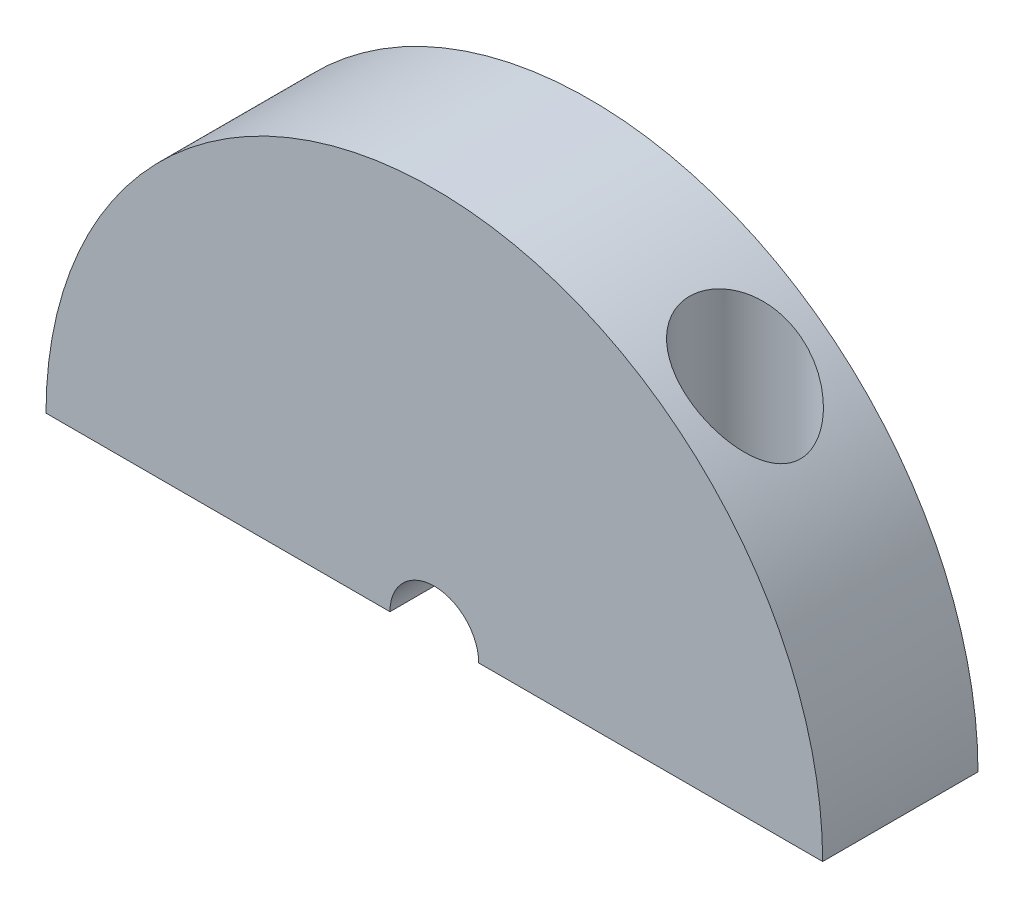
SolidWorks part; units mm, degrees
ref_plane "Plan de face" through (0, 0, 0) normal (0, 0, 1) x (1, 0, 0)
ref_plane "Plan de dessus" through (0, 0, 0) normal (0, 1, 0) x (1, 0, 0)
ref_plane "Plan de droite" through (0, 0, 0) normal (1, 0, 0) x (0, 0, -1)
sketch "Esquisse1" plane through (0, 0, 0) normal (0, 0, 1) x (1, 0, 0)
  line L0 (-1.7321, 1) -> (1.7321, 1)
  line L1 (0, 0) -> (17.5, 0)
  line L6 (17.5, 0) -> (-17.5, 0)
  circle A1 centre (0, 0) radius 2
  circle A2 centre (0, 0) radius 17.5
  dimension "D2" = 4
  dimension "D7" = 35
  dimension "D3" = 1
extrude "Boss.-Extru.1" add sketch "Esquisse1" along normal blind 5
sketch "Esquisse3" plane through (0, 0, 0) normal (0, 0, -1) x (-1, 0, 0)
  line L0 (0, 17.5) -> (0, -17.5)
  line L1 (-17.5, 0) -> (17.5, 0)
  circle A0 centre (0, 0) radius 17.5
  circle A1 centre (0, 0) radius 2
  point P9 (0, 0)
  arc M3 (1.7321, 1) -> (2, 0) centre (0, 0) cw
  arc M5 (17.5, 0) -> (-17.5, 0) centre (0, 0) ccw
  line M9 (-17.5, 0) -> (-2, 0)
  arc M10 (-2, 0) -> (-1.7321, 1) centre (0, 0) cw
  line M11 (2, 0) -> (17.5, 0)
extrude "Boss.-Extru.3" add sketch "Esquisse3" along normal blind 2 contours A1 L0 M5 M9 M10 | A1 L0 M3 M11 M5
sketch "Esquisse5" plane through (0, 0, 0) normal (0, -1, 0) x (1, 0, 0)
  line L0 (2, 5) -> (17.5, 5) construction
  line L1 (-2, 5) -> (-17.5, 5) construction
  line L2 (-17.5, 5) -> (-17.5, -2) construction
  line L3 (17.5, 5) -> (17.5, -2) construction
  circle A0 centre (-10.5, 1.5) radius 0.5
  circle A1 centre (10.5, 1.5) radius 2.5
  dimension "D1" = 1
  dimension "D2" = 5
  dimension "D3" = 3.5
  dimension "D4" = 3.5
  dimension "D5" = 7
  dimension "D6" = 7
extrude "Enlèv. mat.-Extru.1" cut sketch "Esquisse5" against normal blind 2
sketch "Esquisse7" plane through (0, 2, 0) normal (0, -1, 0) x (1, 0, 0)
  circle A0 centre (10.5, 1.5) radius 2.5
extrude "Enlèv. mat.-Extru.2" cut sketch "Esquisse7" against normal through all
sketch "Esquisse8" plane through (0, 0, -2) normal (0, 0, -1) x (-1, 0, 0)
  circle A0 centre (0, 0) radius 2
extrude "Enlèv. mat.-Extru.3" cut sketch "Esquisse8" against normal through all
